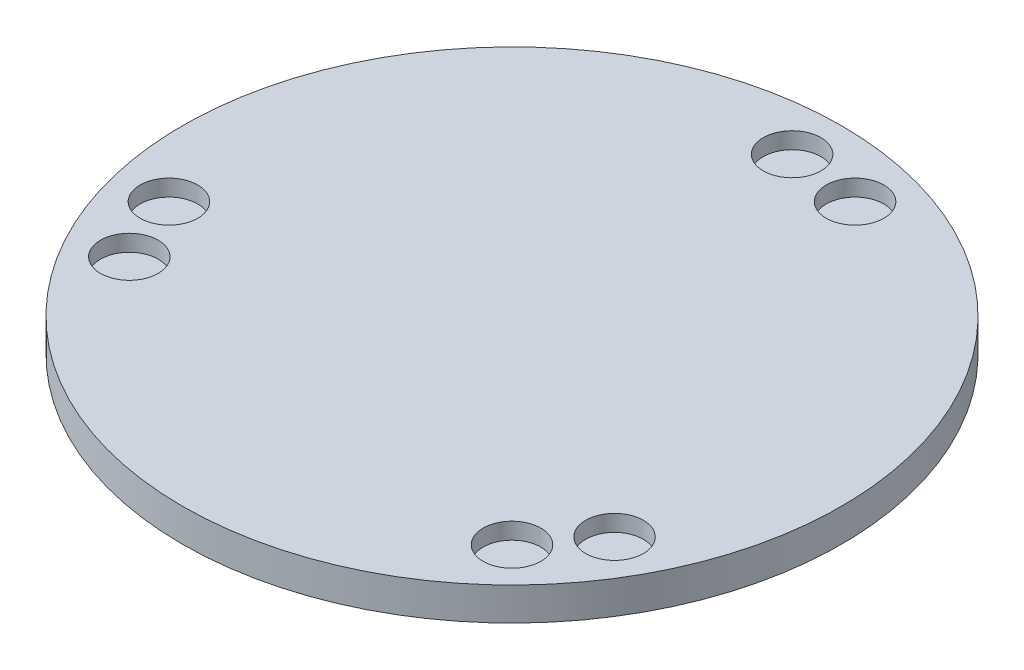
SolidWorks part; units mm, degrees
material "6061 Alloy"
ref_plane "Front" through (0, 0, 0) normal (0, 0, 1) x (1, 0, 0)
ref_plane "Top" through (0, 0, 0) normal (0, 1, 0) x (1, 0, 0)
ref_plane "Right" through (0, 0, 0) normal (1, 0, 0) x (0, 0, -1)
sketch "Sketch1" plane through (0, 0, 0) normal (0, 1, 0) x (1, 0, 0)
  circle A0 centre (0, 0) radius 200
extrude "Extrude1" add sketch "Sketch1" against normal blind 20
sketch "Sketch2" plane through (0, 0, 0) normal (0, 1, 0) x (1, 0, 0)
  line L0 (0, 0) -> (43.9992, 164.2074) construction
  line L1 (0, -11) -> (0, 11) construction
  circle A0 centre (0, 0) radius 170 construction
  circle A1 centre (0, 170) radius 17.5
  circle A2 centre (43.9992, 164.2074) radius 17.5
  circle A3 centre (147.2243, -85) radius 17.5
  circle A4 centre (120.2082, -120.2082) radius 17.5
  circle A5 centre (-147.2243, -85) radius 17.5
  circle A6 centre (-164.2074, -43.9992) radius 17.5
  circle A7 centre (0, 0) radius 200 construction
  dimension "D1" = 30
  dimension "D2" = 15
extrude "Cut-Extrude1" cut sketch "Sketch2" along direction (0, 1, 0) on the side against the normal offset from surface (10 mm away) 10
sketch "Sketch3" plane through (0, 0, 0) normal (0, 1, 0) x (1, 0, 0)
  circle A0 centre (0, 0) radius 100 construction
  circle A1 centre (0, 0) radius 75 construction
